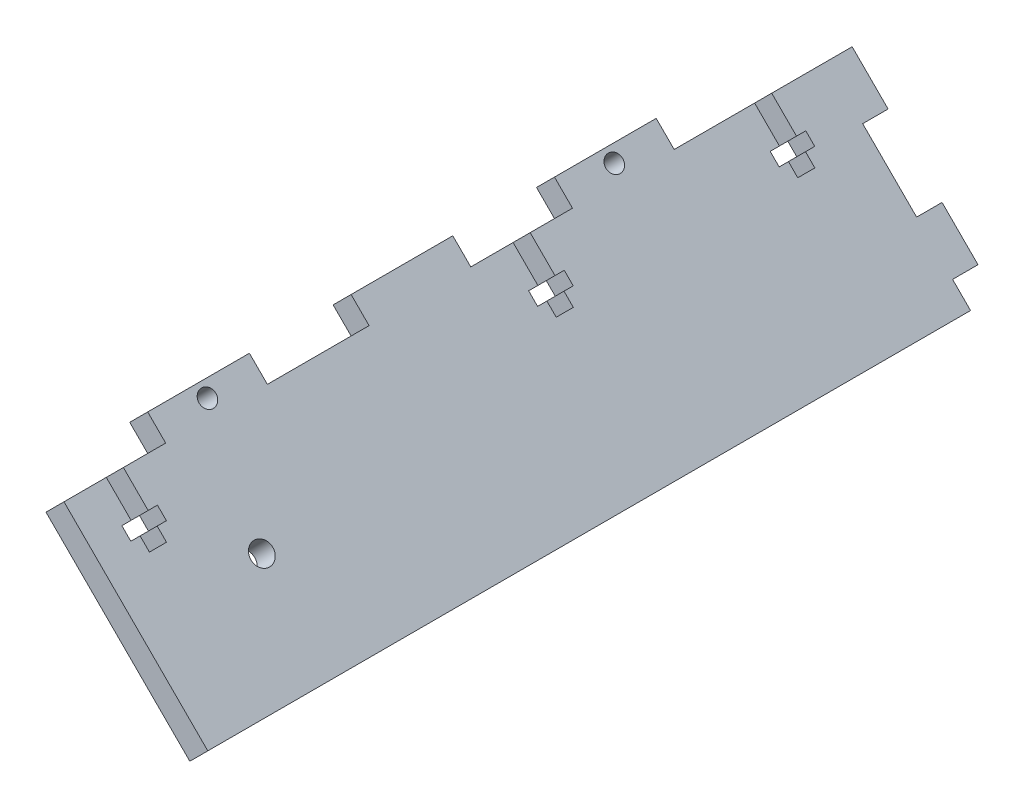
SolidWorks part; units mm, degrees
ref_plane "Front Plane" through (0, 0, 0) normal (0, 0, 1) x (1, 0, 0)
ref_plane "Top Plane" through (0, 0, 0) normal (0, 1, 0) x (1, 0, 0)
ref_plane "Right Plane" through (0, 0, 0) normal (1, 0, 0) x (0, 0, -1)
sketch "Sketch1" plane through (0, 0, 0) normal (0, 0, 1) x (1, 0, 0)
  line L0 (-105.5101, 43.1479) -> (-54.0999, -8.2622) construction
  line L1 (-21.1674, -45.6848) -> (-64.2712, -2.5811) construction
  line L2 (-59.7811, 1.9091) -> (-16.6773, -41.1947) construction
  line L3 (-73.6381, 43.6049) -> (-37.7171, 7.6839)
  line L4 (-73.6381, 43.6049) -> (-69.148, 48.095)
  line L5 (-37.7171, 7.6839) -> (-33.2269, 12.174)
  line L6 (-69.148, 48.095) -> (-33.2269, 12.174)
  line L7 (-70.046, -24.645) -> (-105.967, 11.276) construction
  line L8 (-74.5361, -29.1352) -> (-70.046, -24.645) construction
extrude "Boss-Extrude1" add sketch "Sketch1" along normal up to surface (190.5 mm away)
sketch "Sketch2" plane through (-58.6215, 58.6215, 0) normal (-0.7071, 0.7071, 0) x (0, 0, 1)
  line L0 (190.5, -14.8867) -> (0, -14.8867) construction
  line L1 (165.1, -14.8867) -> (139.7, -14.8867)
  line L2 (165.1, -14.8867) -> (165.1, -21.2367)
  line L3 (165.1, -21.2367) -> (139.7, -21.2367)
  line L4 (139.7, -14.8867) -> (139.7, -21.2367)
  line L5 (190.5, -21.2367) -> (0, -21.2367) construction
  dimension "D1" = 25.4
  dimension "D2" = 25.4
extrude "Boss-Extrude2" add sketch "Sketch2" along normal blind 6.35
pattern_linear "LPattern1" count 3 spacing 50.8 along (0, 0, -1) of "Boss-Extrude2"
sketch "Sketch3" plane through (0, 0, 0) normal (0, 0, -1) x (-1, 0, 0)
  line L0 (73.6381, 43.6049) -> (64.6578, 34.6246)
  line L1 (73.6381, 43.6049) -> (37.7171, 7.6839) construction
  line L2 (64.6578, 34.6246) -> (60.1677, 39.1148)
  line L3 (33.2269, 12.174) -> (69.148, 48.095) construction
  line L4 (60.1677, 39.1148) -> (69.148, 48.095)
  line L5 (69.148, 48.095) -> (73.6381, 43.6049)
  dimension "D1" = 12.7
extrude "Boss-Extrude3" add sketch "Sketch3" along normal blind 6.35
pattern_linear "LPattern2" count 2 spacing 31.75 along (0.7071, -0.7071, 0) of "Boss-Extrude3"
sketch "Sketch4" plane through (-10.5265, -10.5265, 0) normal (0.7071, 0.7071, 0) x (0, 0, -1)
  circle A0 centre (-159.0375, 57.5033) radius 2.7305
extrude "Cut-Extrude1" cut sketch "Sketch4" against normal through all
sketch "Sketch5" plane through (-10.5265, -10.5265, 0) normal (0.7071, 0.7071, 0) x (0, 0, -1)
  line L0 (-177.8, 82.9033) -> (-177.8, 68.4326) construction
  line L1 (-190.5, 82.9033) -> (-165.1, 82.9033) construction
  line L2 (-76.2, 82.9033) -> (-76.2, 62.5112) construction
  line L3 (-88.9, 82.9033) -> (-63.5, 82.9033) construction
  line L4 (-15.875, 82.9033) -> (-15.875, 66.2052) construction
  line L5 (-38.1, 82.9033) -> (6.35, 82.9033) construction
  line L6 (-38.1412, 82.9033) -> (0, 82.9033) construction
  line B0 (-175.6664, 82.9033) -> (-179.9336, 82.9033)
  line B1 (-179.9336, 70.9653) -> (-182.245, 70.9653)
  line B2 (-182.245, 70.9653) -> (-182.245, 74.1403)
  line B3 (-182.245, 74.1403) -> (-179.9336, 74.1403)
  line B4 (-179.9336, 74.1403) -> (-179.9336, 82.9033)
  line B5 (-179.9336, 70.9653) -> (-179.9336, 67.6633)
  line B6 (-179.9336, 67.6633) -> (-175.6664, 67.6633)
  line B7 (-175.6664, 70.9653) -> (-175.6664, 67.6633)
  line B8 (-175.6664, 74.1403) -> (-175.6664, 82.9033)
  line B9 (-173.355, 74.1403) -> (-175.6664, 74.1403)
  line B10 (-173.355, 70.9653) -> (-173.355, 74.1403)
  line B11 (-175.6664, 70.9653) -> (-173.355, 70.9653)
  line B12 (-74.0664, 82.9033) -> (-78.3336, 82.9033)
  line B13 (-78.3336, 70.9653) -> (-80.645, 70.9653)
  line B14 (-80.645, 70.9653) -> (-80.645, 74.1403)
  line B15 (-80.645, 74.1403) -> (-78.3336, 74.1403)
  line B16 (-78.3336, 74.1403) -> (-78.3336, 82.9033)
  line B17 (-78.3336, 70.9653) -> (-78.3336, 67.6633)
  line B18 (-78.3336, 67.6633) -> (-74.0664, 67.6633)
  line B19 (-74.0664, 70.9653) -> (-74.0664, 67.6633)
  line B20 (-74.0664, 74.1403) -> (-74.0664, 82.9033)
  line B21 (-71.755, 74.1403) -> (-74.0664, 74.1403)
  line B22 (-71.755, 70.9653) -> (-71.755, 74.1403)
  line B23 (-74.0664, 70.9653) -> (-71.755, 70.9653)
  line B24 (-13.7414, 82.9033) -> (-18.0086, 82.9033)
  line B25 (-18.0086, 70.9653) -> (-20.32, 70.9653)
  line B26 (-20.32, 70.9653) -> (-20.32, 74.1403)
  line B27 (-20.32, 74.1403) -> (-18.0086, 74.1403)
  line B28 (-18.0086, 74.1403) -> (-18.0086, 82.9033)
  line B29 (-18.0086, 70.9653) -> (-18.0086, 67.6633)
  line B30 (-18.0086, 67.6633) -> (-13.7414, 67.6633)
  line B31 (-13.7414, 70.9653) -> (-13.7414, 67.6633)
  line B32 (-13.7414, 74.1403) -> (-13.7414, 82.9033)
  line B33 (-11.43, 74.1403) -> (-13.7414, 74.1403)
  line B34 (-11.43, 70.9653) -> (-11.43, 74.1403)
  line B35 (-13.7414, 70.9653) -> (-11.43, 70.9653)
sketch_block_instance "TSlot-1"
sketch_block "TSlot" parameters "D1"=3.302, "D2"=3.175
sketch_block_instance "TSlot-2"
sketch_block_instance "TSlot-3"
extrude "Cut-Extrude2" cut sketch "Sketch5" against normal through all
sketch "Sketch6" plane through (-15.0166, -15.0166, 0) normal (-0.7071, -0.7071, 0) x (0, 0, 1)
  line L0 (150.287, 89.2533) -> (154.5542, 82.9033) construction
  line L1 (139.7, 89.2533) -> (165.1, 89.2533) construction
  line L2 (150.287, 89.2533) -> (150.287, 82.9033) construction
  line L3 (154.5542, 89.2533) -> (150.287, 82.9033) construction
  line L4 (154.5542, 82.9033) -> (154.5542, 89.2533) construction
  line L5 (48.687, 89.2533) -> (52.9542, 82.9033) construction
  line L6 (38.1, 89.2533) -> (63.5, 89.2533) construction
  line L7 (48.687, 89.2533) -> (48.687, 82.9033) construction
  line L8 (52.9542, 89.2533) -> (48.687, 82.9033) construction
  line L9 (52.9542, 82.9033) -> (52.9542, 89.2533) construction
  circle A0 centre (152.4206, 86.0783) radius 2.0955
  circle A1 centre (50.8206, 86.0783) radius 2.0955
  dimension "D1" = 4.191
extrude "Cut-Extrude3" cut sketch "Sketch6" against normal through all
